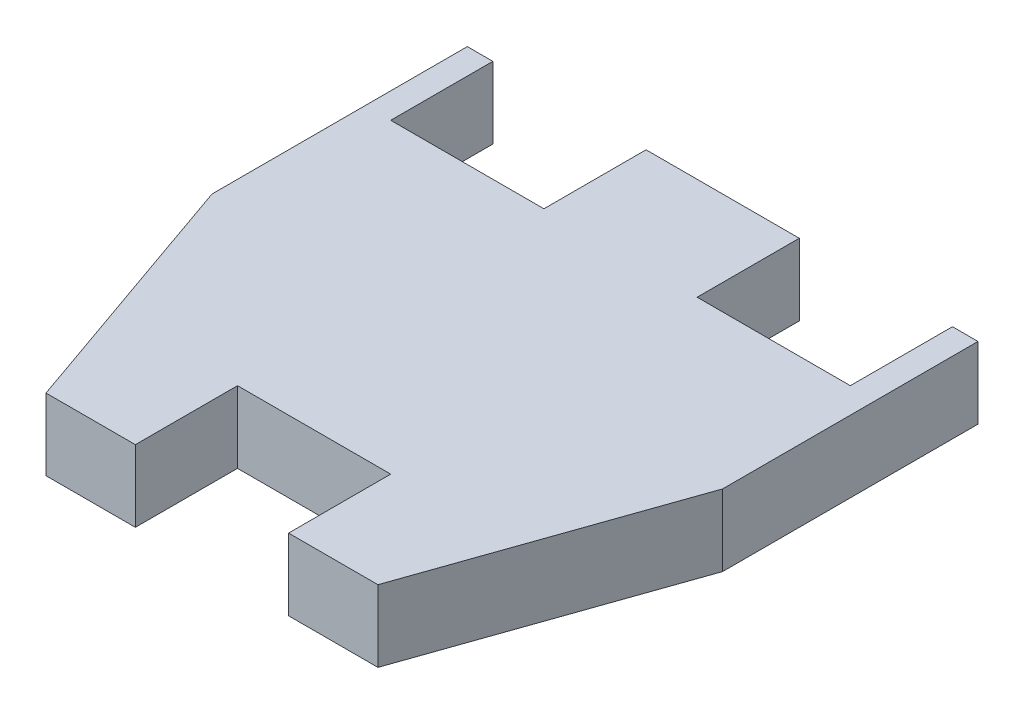
SolidWorks part; units mm, degrees
ref_plane "Front Plane" through (0, 0, 0) normal (0, 0, 1) x (1, 0, 0)
ref_plane "Top Plane" through (0, 0, 0) normal (0, 1, 0) x (1, 0, 0)
ref_plane "Right Plane" through (0, 0, 0) normal (1, 0, 0) x (0, 0, -1)
sketch "Sketch1" plane through (0, 0, 0) normal (0, 1, 0) x (1, 0, 0)
  line L1 (-50, 50) -> (50, 50)
  line L2 (-50, 50) -> (-50, -50)
  line L3 (-50, -50) -> (50, -50)
  line L4 (50, 50) -> (50, -50)
  line L5 (-50, 50) -> (50, -50) construction
  line L6 (-50, -50) -> (50, 50) construction
  line L7 (-45, 50) -> (-15, 50)
  line L8 (-45, 50) -> (-45, 30)
  line L9 (-45, 30) -> (-15, 30)
  line L10 (-15, 50) -> (-15, 30)
  line L11 (15, 50) -> (45, 50)
  line L12 (15, 50) -> (15, 30)
  line L13 (15, 30) -> (45, 30)
  line L14 (45, 50) -> (45, 30)
  line L15 (-15, -30) -> (15, -30)
  line L16 (-15, -30) -> (-15, -50)
  line L17 (-15, -50) -> (15, -50)
  line L18 (15, -30) -> (15, -50)
  point P0 (0, 0)
  point P14 (15, 40)
  dimension "D1" = 100
  dimension "D2" = 100
  dimension "D3" = 20
  dimension "D4" = 30
  dimension "D5" = 30
  dimension "D6" = 20
  dimension "D7" = 30
  dimension "D8" = 5
  dimension "D9" = 30
  dimension "D10" = 20
  dimension "D11" = 35
extrude "Boss-Extrude1" add sketch "Sketch1" along normal blind 14.0278 contours L15 L18 L3 L4 L1 L14 L13 L12 L10 L9 L8 L2 L16
sketch "Sketch2" plane through (15, 0, 0) normal (-1, 0, 0) x (0, 0, 1)
  line L0 (40.2052, 11.5651) -> (40.2052, 1.5651)
  arc A1 (40.2052, 1.5651) -> (40.2052, 11.5651) centre (40.2052, 6.5651) cw
  dimension "D1" = 5
revolve "Revolve1" add sketch "Sketch2" angle 360 about L0
sketch "Sketch3" plane through (0, 0, 0) normal (0, 1, 0) x (1, 0, 0)
  line L0 (-50, 0) -> (-32.5, -50)
  line L1 (-50, 50) -> (-50, -50) construction
  line L2 (-50, -50) -> (-15, -50) construction
  line L3 (-32.5, -50) -> (-50, -50)
  line L4 (-50, -50) -> (-50, 0)
  dimension "D1" = 50
  dimension "D2" = 17.5
  dimension "D3" = 52.9741
extrude "Cut-Extrude1" cut sketch "Sketch3" along normal blind 16
sketch "Sketch4" plane through (0, 0, 0) normal (0, 1, 0) x (1, 0, 0)
  line L0 (32.5, -50) -> (50, 0)
  line L1 (15, -50) -> (50, -50) construction
  line L2 (50, 50) -> (50, -50) construction
  line L3 (50, 0) -> (50, -50)
  line L4 (50, -50) -> (32.5, -50)
  dimension "D1" = 50
  dimension "D2" = 52.9741
  dimension "D3" = 17.5
extrude "Cut-Extrude2" cut sketch "Sketch4" along normal blind 16
